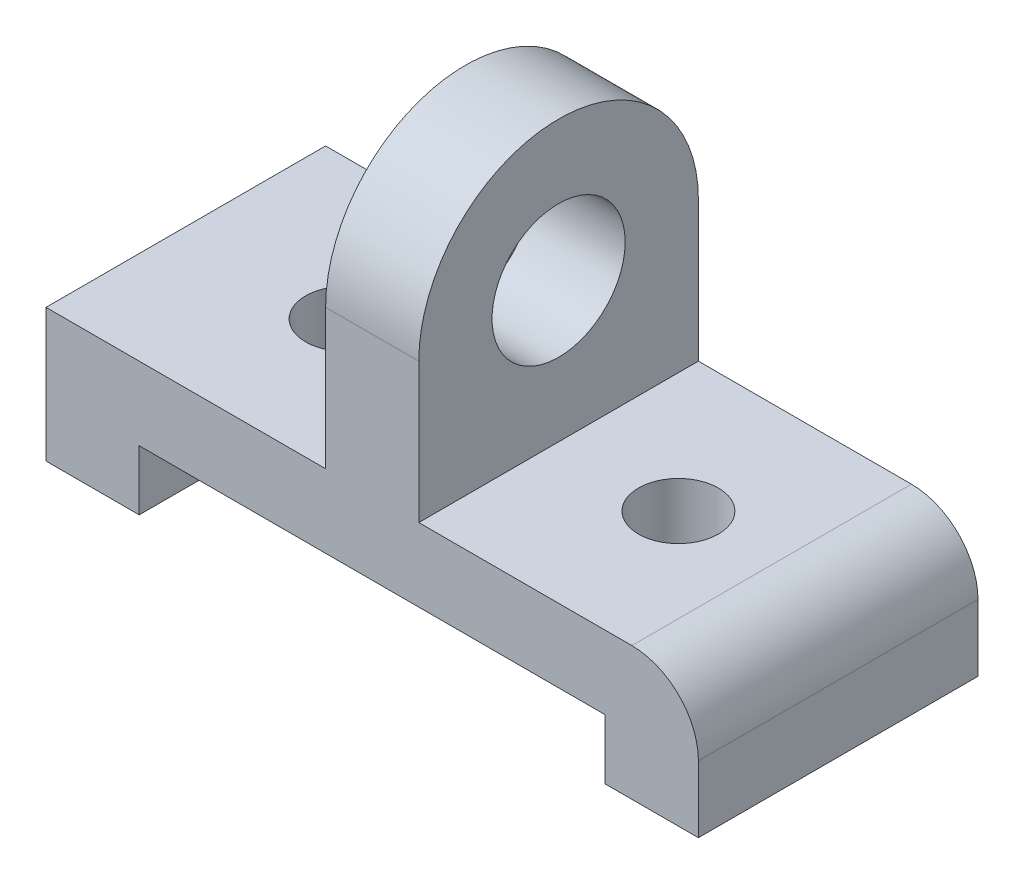
SolidWorks part; units mm, degrees
ref_plane "Front Plane" through (0, 0, 0) normal (0, 0, 1) x (1, 0, 0)
ref_plane "Top Plane" through (0, 0, 0) normal (0, 1, 0) x (1, 0, 0)
ref_plane "Right Plane" through (0, 0, 0) normal (1, 0, 0) x (0, 0, -1)
sketch "Sketch1" plane through (0, 0, 0) normal (0, 1, 0) x (1, 0, 0)
  line L1 (-49, 21) -> (49, 21)
  line L2 (-49, 21) -> (-49, -21)
  line L3 (-49, -21) -> (49, -21)
  line L4 (49, 21) -> (49, -21)
  line L5 (-49, 21) -> (49, -21) construction
  line L6 (-49, -21) -> (49, 21) construction
  point P0 (0, 0)
  dimension "D1" = 98
  dimension "D2" = 42
extrude "Boss-Extrude1" add sketch "Sketch1" along normal blind 20
sketch "Sketch2" plane through (0, 0, 21) normal (0, 0, 1) x (1, 0, 0)
  line L0 (-49, 0) -> (49, 0) construction
  line L1 (-35, 0) -> (35, 0)
  line L2 (-35, 0) -> (-35, 9)
  line L3 (-35, 9) -> (35, 9)
  line L4 (35, 0) -> (35, 9)
  line L5 (-49, 20) -> (-49, 0) construction
  line L6 (49, 20) -> (49, 0) construction
  dimension "D1" = 14
  dimension "D2" = 9
  dimension "D3" = 14
extrude "Cut-Extrude1" cut sketch "Sketch2" against normal through all
sketch "Sketch3" plane through (0, 20, 0) normal (0, 1, 0) x (1, 0, 0)
  line L0 (-49, -21) -> (49, -21) construction
  line L1 (-7, 21) -> (7, 21)
  line L2 (-7, 21) -> (-7, -21)
  line L3 (-7, -21) -> (7, -21)
  line L4 (7, 21) -> (7, -21)
  line L5 (-7, 21) -> (7, -21) construction
  line L6 (-7, -21) -> (7, 21) construction
  point P0 (0, 0)
  dimension "D1" = 14
extrude "Boss-Extrude2" add sketch "Sketch3" along normal blind 21
sketch "Sketch4" plane through (7, 0, 0) normal (1, 0, 0) x (0, 0, -1)
  line L0 (-21, 41) -> (21, 41) construction
  circle A0 centre (0, 41) radius 21
extrude "Boss-Extrude3" add sketch "Sketch4" against normal blind 14 contours A0
sketch "Sketch5" plane through (0, 20, 0) normal (0, 1, 0) x (1, 0, 0)
  line L0 (49, -21) -> (49, 21) construction
  line L2 (7, -21) -> (49, -21) construction
  circle A0 centre (25, 0) radius 6
  point P6 (22.4235, -21)
  point P7 (0, 0)
  dimension "D3" = 12
  dimension "D1" = 24
  dimension "D2" = 21
extrude "Cut-Extrude2" cut sketch "Sketch5" against normal through all
mirror "Mirror1" about plane through (0, 0, 0) normal (1, 0, 0) of "Cut-Extrude2"
fillet "Fillet3" radius 10 1 edges at (49, 20, 0)
sketch "Sketch6" plane through (7, 0, 0) normal (1, 0, 0) x (0, 0, -1)
  line L0 (-21, 20) -> (21, 20) construction
  line L1 (21, 41) -> (21, 20) construction
  circle A0 centre (0, 41) radius 10
  dimension "D1" = 20
  dimension "D2" = 21
  dimension "D3" = 21
extrude "Cut-Extrude3" cut sketch "Sketch6" against normal blind 14
